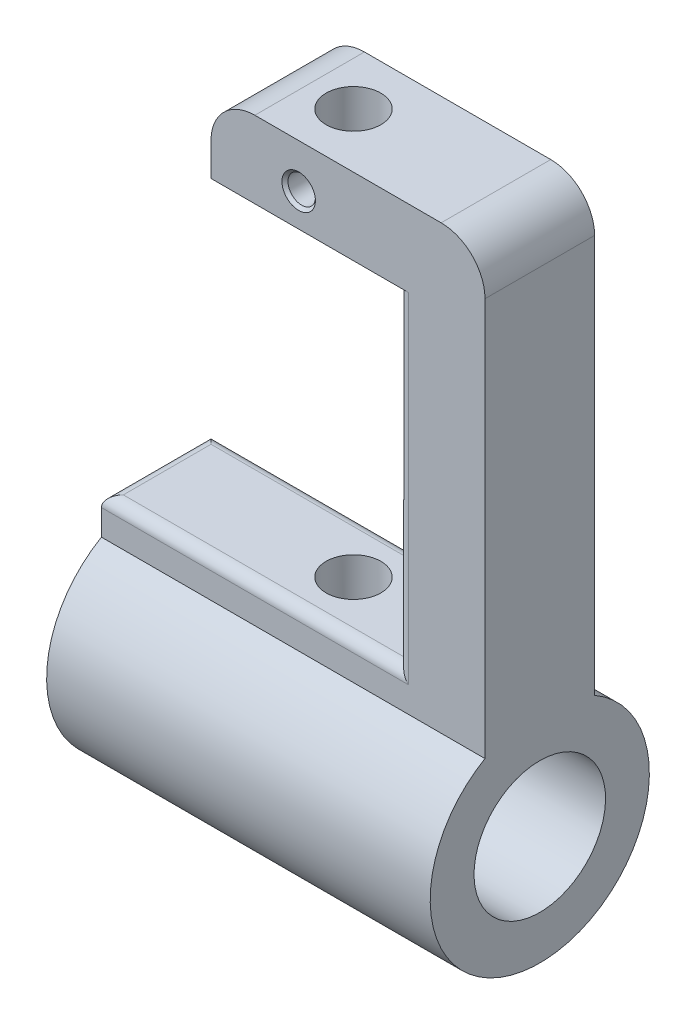
SolidWorks part; units mm, degrees
ref_plane "前视基准面" through (0, 0, 0) normal (0, 0, 1) x (1, 0, 0)
ref_plane "上视基准面" through (0, 0, 0) normal (0, 1, 0) x (1, 0, 0)
ref_plane "右视基准面" through (0, 0, 0) normal (1, 0, 0) x (0, 0, -1)
other "Configuration Table"
sketch "草图1" plane through (0, 0, 0) normal (0, 0, 1) x (1, 0, 0)
  line L2 (-8, 8) -> (-8, 38)
  line L5 (-21, 45) -> (-4, 45)
  line L6 (0, 41) -> (0, 0)
  line L8 (-25, 38) -> (-25, 41)
  line L10 (-8, 38) -> (-25, 38)
  line L12 (0, 0) -> (-35, 0)
  line L13 (-35, 0) -> (-35, 8)
  line L14 (-35, 8) -> (-8, 8)
  arc A0 (-4, 45) -> (0, 41) centre (-4, 41) cw
  arc A1 (-21, 45) -> (-25, 41) centre (-21, 41) ccw
  point P0 (0, 0)
  point P13 (0, 45)
  point P16 (-25, 45)
  dimension "D6" = 4
  dimension "D8" = 4
  dimension "D1" = 8
  dimension "D2" = 30
  dimension "D3" = 25
  dimension "D4" = 7
  dimension "D7" = 35
  dimension "D9" = 8
extrude "凸台-拉伸1" add sketch "草图1" along normal blind 10
sketch "草图5" plane through (0, 0, 0) normal (1, 0, 0) x (0, 0, -1)
  line L0 (-10, 0) -> (0, 0) construction
  line L2 (-10, 0) -> (-10, 41) construction
  line L3 (-5, 6) -> (-5, -4) construction
  circle A0 centre (-5, -4) radius 10
  circle A1 centre (-5, -4) radius 6 construction
  dimension "D3" = 20
  dimension "D5" = 5
  dimension "D1" = 4
  dimension "D2" = 10
extrude "凸台-拉伸2" add sketch "草图5" against normal through all
sketch "草图7" plane through (0, 0, 0) normal (1, 0, 0) x (0, 0, -1)
  circle A0 centre (-5, -4) radius 6
  dimension "D1" = 12
extrude "切除-拉伸1" cut sketch "草图7" against normal through all
sketch "草图8" plane through (0, 45, 0) normal (0, 1, 0) x (1, 0, 0)
  line L6 (-25, 0) -> (-17, 0) construction
  line L7 (-25, 0) -> (-25, -10) construction
  line L8 (-25, -10) -> (-17, -10) construction
  line L9 (-17, 0) -> (-17, -10) construction
  circle A1 centre (-17, -5) radius 2.5
  dimension "D3" = 5
  dimension "D2" = 5
  dimension "D1" = 8
extrude "切除-拉伸3" cut sketch "草图8" against normal blind 41
fillet "圆角3" radius 1 5 edges at (-8, 23, 0) (-8, 23, 10) (-21.5, 8, 0) (-21.5, 8, 10) (-35, 8, 5)
hole_wizard "M3 螺纹孔2" positions "3D草图2" profile "草图10" tap size "M3" standard "GB"
sketch3d "3D草图2"
  line L0 (-25, 38, 10) -> (-7, 38, 10) construction
  line L1 (-25, 41, 10) -> (-25, 38, 10) construction
  point P0 (-17, 41, 10)
  dimension "D1" = 3
  dimension "D2" = 8
sketch "草图10" plane through (-17, 41, 10) normal (1, 0, 0) x (0, -1, 0)
  line L0 (0, 0) -> (0, 7.7511)
  line L1 (0, 7.7511) -> (1.25, 7)
  line L2 (1.25, 7) -> (1.25, 0.275)
  line L3 (1.25, 0.275) -> (1.525, 0)
  line L5 (1.525, 0) -> (0, 0)
  line L6 (-1.25, 0.275) -> (-1.525, 0) construction
  line L10 (0, 7.7511) -> (-1.25, 7) construction
  line L11 (0, -6.35) -> (0, 107.95) construction
  dimension "螺纹孔钻头直径" = 2.5
  dimension "螺纹孔钻头深度" = 7
  dimension "近端锥形沉头孔直径" = 3.05
  dimension "近端锥形沉头孔角度" = 90
  dimension "导头角度" = 118
cosmetic thread "孔螺蚊线2" parameters "D1"=4.5, "D2"=3
